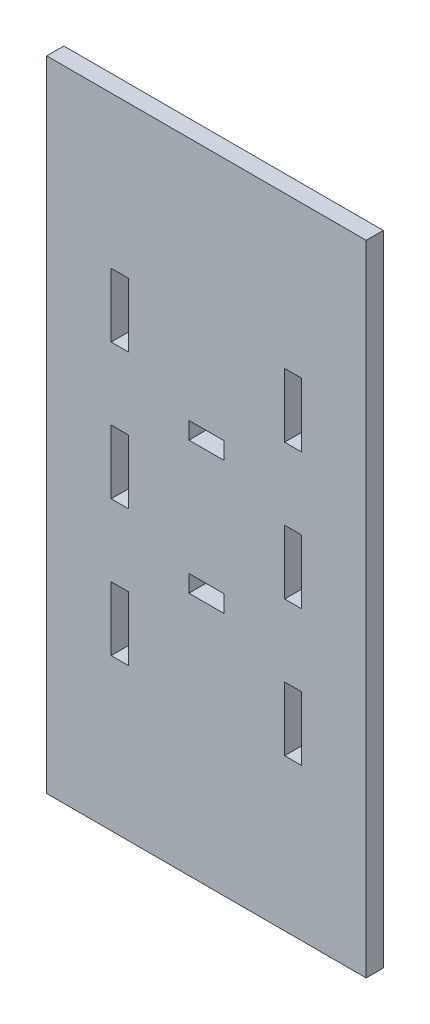
SolidWorks part; units mm, degrees
ref_plane "Front Plane" through (0, 0, 0) normal (0, 0, 1) x (1, 0, 0)
ref_plane "Top Plane" through (0, 0, 0) normal (0, 1, 0) x (1, 0, 0)
ref_plane "Right Plane" through (0, 0, 0) normal (1, 0, 0) x (0, 0, -1)
sketch "Model" plane through (0, 0, 0) normal (0, 0, 1) x (1, 0, 0)
  line L20 (44.5, 76.575) -> (55.5, 76.575)
  line L21 (55.5, 76.575) -> (55.5, 81.925)
  line L22 (55.5, 81.925) -> (44.5, 81.925)
  line L23 (44.5, 81.925) -> (44.5, 76.575)
  line L24 (44.5, 118.075) -> (55.5, 118.075)
  line L25 (55.5, 118.075) -> (55.5, 123.425)
  line L26 (55.5, 123.425) -> (44.5, 123.425)
  line L27 (44.5, 123.425) -> (44.5, 118.075)
  line L28 (20.17, 67.5) -> (20.17, 47.5)
  line L29 (20.17, 47.5) -> (25.52, 47.5)
  line L30 (25.52, 47.5) -> (25.52, 67.5)
  line L31 (25.52, 67.5) -> (20.17, 67.5)
  line L32 (20.17, 110) -> (20.17, 90)
  line L33 (20.17, 90) -> (25.52, 90)
  line L34 (25.52, 90) -> (25.52, 110)
  line L35 (25.52, 110) -> (20.17, 110)
  line L36 (20.17, 152.5) -> (20.17, 132.5)
  line L37 (20.17, 132.5) -> (25.52, 132.5)
  line L38 (25.52, 132.5) -> (25.52, 152.5)
  line L39 (25.52, 152.5) -> (20.17, 152.5)
  line L40 (74.48, 152.5) -> (74.48, 132.5)
  line L41 (74.48, 132.5) -> (79.83, 132.5)
  line L42 (79.83, 132.5) -> (79.83, 152.5)
  line L43 (79.83, 152.5) -> (74.48, 152.5)
  line L44 (74.48, 110) -> (74.48, 90)
  line L45 (74.48, 90) -> (79.83, 90)
  line L46 (79.83, 90) -> (79.83, 110)
  line L47 (79.83, 110) -> (74.48, 110)
  line L48 (74.48, 67.5) -> (74.48, 47.5)
  line L49 (74.48, 47.5) -> (79.83, 47.5)
  line L50 (79.83, 47.5) -> (79.83, 67.5)
  line L51 (79.83, 67.5) -> (74.48, 67.5)
  line L52 (0, 200) -> (0, 0)
  line L53 (100, 200) -> (0, 200)
  line L54 (100, 0) -> (100, 200)
  line L55 (0, 0) -> (100, 0)
extrude "Boss-Extrude1" add sketch "Model" along normal blind 5.35
